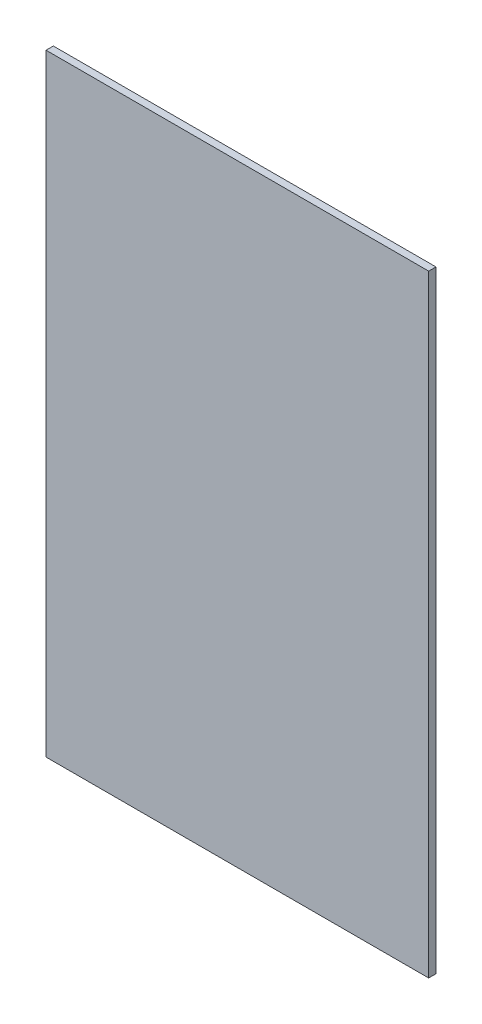
SolidWorks part; units mm, degrees
ref_plane "Front Plane" through (0, 0, 0) normal (0, 0, 1) x (1, 0, 0)
ref_plane "Top Plane" through (0, 0, 0) normal (0, 1, 0) x (1, 0, 0)
ref_plane "Right Plane" through (0, 0, 0) normal (1, 0, 0) x (0, 0, -1)
sketch "Sketch1" plane through (0, 0, 0) normal (0, 0, 1) x (1, 0, 0)
  line L1 (0, 0) -> (420, 0)
  line L2 (0, 0) -> (0, 672)
  line L3 (0, 672) -> (420, 672)
  line L4 (420, 0) -> (420, 672)
  dimension "D1" = 672
  dimension "D2" = 420
extrude "Boss-Extrude1" add sketch "Sketch1" along normal blind 8
